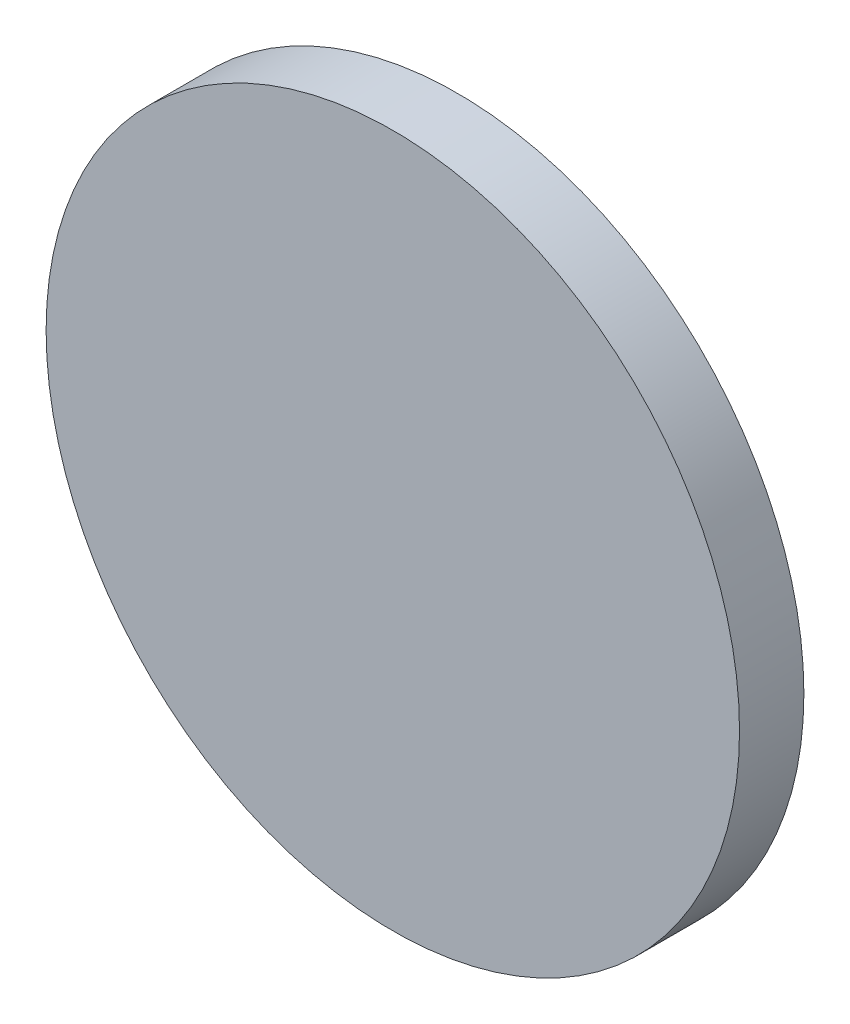
SolidWorks part; units mm, degrees
ref_plane "Front" through (0, 0, 0) normal (0, 0, 1) x (1, 0, 0)
ref_plane "Top" through (0, 0, 0) normal (0, 1, 0) x (1, 0, 0)
ref_plane "Right" through (0, 0, 0) normal (1, 0, 0) x (0, 0, -1)
sketch "Sketch1" plane through (0, 0, 0) normal (0, 0, 1) x (1, 0, 0)
  circle A0 centre (0, 0) radius 13.6823
extrude "Extrude1" add sketch "Sketch1" along normal blind 2.54
